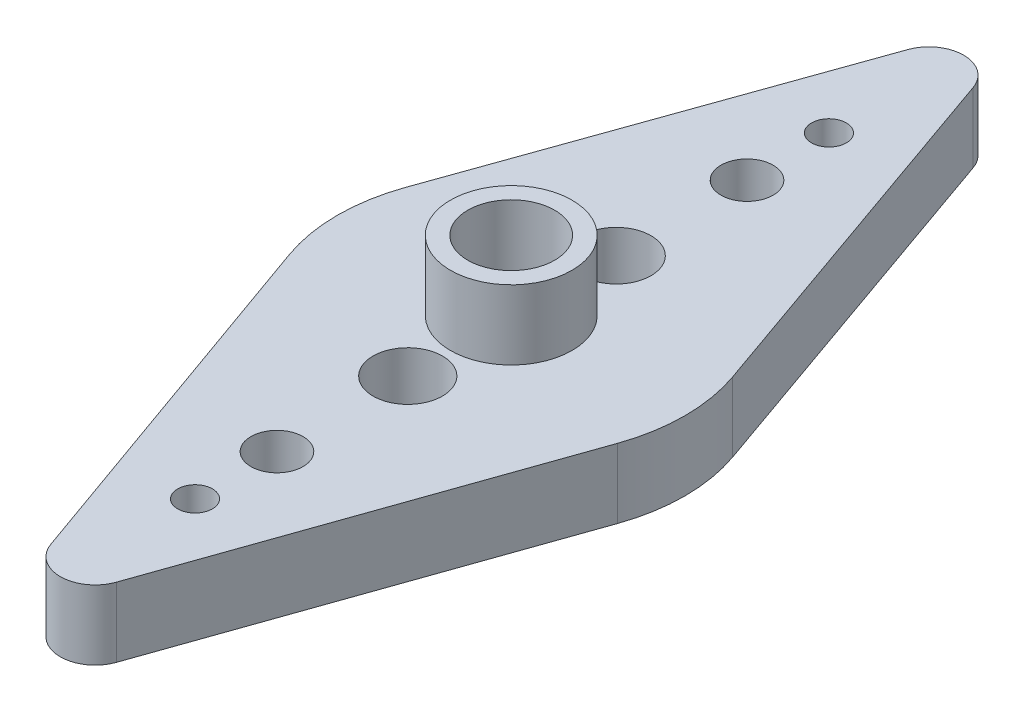
SolidWorks part; units mm, degrees
ref_plane "Front Plane" through (0, 0, 0) normal (0, 0, 1) x (1, 0, 0)
ref_plane "Top Plane" through (0, 0, 0) normal (0, 1, 0) x (1, 0, 0)
ref_plane "Right Plane" through (0, 0, 0) normal (1, 0, 0) x (0, 0, -1)
sketch "Sketch1" plane through (0, 0, 0) normal (0, 1, 0) x (1, 0, 0)
  line L0 (-4.711, 1.6754) -> (-0.92, 12.3351)
  line L1 (0.9656, 12.3316) -> (4.7171, 1.658)
  line L2 (-5, 0) -> (5, 0) construction
  line L3 (0.9656, -12.3316) -> (4.7171, -1.658)
  line L4 (-4.711, -1.6754) -> (-0.92, -12.3351)
  arc A0 (-4.711, 1.6754) -> (-4.711, -1.6754) centre (0, 0) ccw
  arc A1 (0.9656, 12.3316) -> (-0.92, 12.3351) centre (0.0222, 12) ccw
  arc A2 (0.9656, -12.3316) -> (-0.92, -12.3351) centre (0.0222, -12) cw
  circle A3 centre (0.0222, 9.1224) radius 0.5
  circle A4 centre (0.0222, 6.765) radius 0.75
  circle A5 centre (0.0222, 3.0002) radius 1
  arc A6 (4.7171, -1.658) -> (4.7171, 1.658) centre (0, 0) ccw
  circle A7 centre (0.0222, -9.1224) radius 0.5
  circle A8 centre (0.0222, -6.765) radius 0.75
  circle A9 centre (0.0222, -3.0002) radius 1
  point P9 (0.0277, 15)
  dimension "D1" = 10
  dimension "D3" = 1
  dimension "D4" = 2
  dimension "D5" = 1.5
  dimension "D6" = 1
  dimension "D2" = 15
extrude "Boss-Extrude1" add sketch "Sketch1" along normal blind 2
sketch "Sketch2" plane through (0, 2, 0) normal (0, 1, 0) x (1, 0, 0)
  circle A0 centre (0, 0) radius 1.25
  dimension "D1" = 2.5
extrude "Extrude-Thin1" add sketch "Sketch2" along normal blind 2 thin
